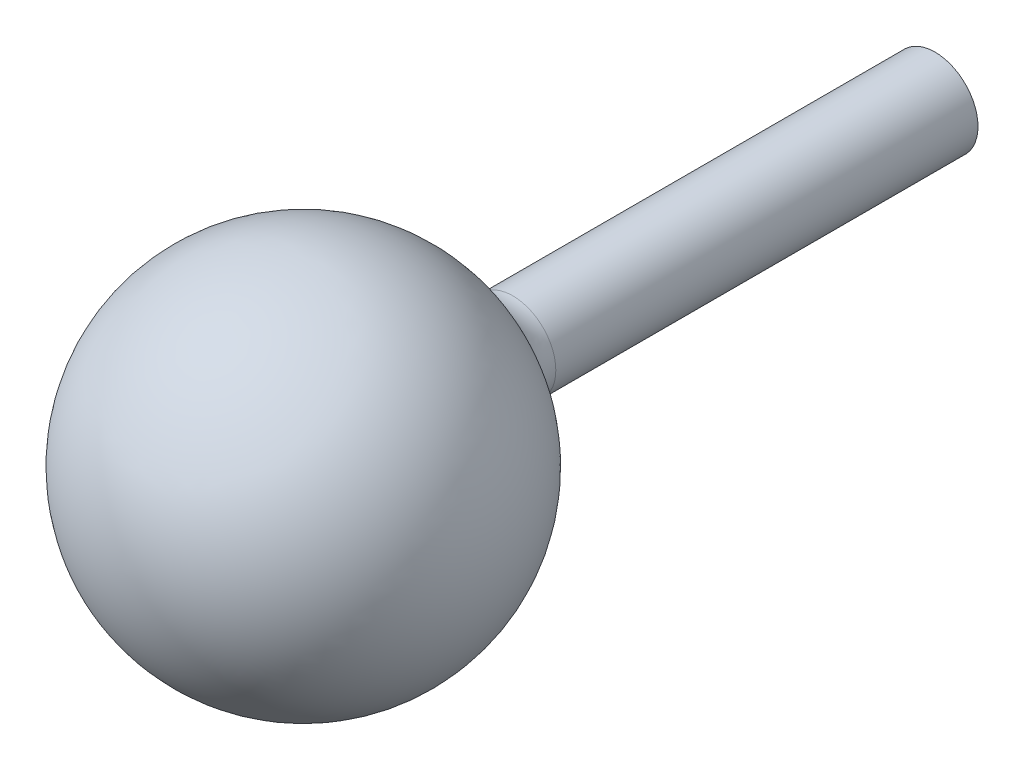
SolidWorks part; units mm, degrees
ref_plane "Front Plane" through (0, 0, 0) normal (0, 0, 1) x (1, 0, 0)
ref_plane "Top Plane" through (0, 0, 0) normal (0, 1, 0) x (1, 0, 0)
ref_plane "Right Plane" through (0, 0, 0) normal (1, 0, 0) x (0, 0, -1)
sketch "Sketch1" plane through (0, 0, 0) normal (0, 0, 1) x (1, 0, 0)
  circle A0 centre (0, 0) radius 6
  dimension "D1" = 12
extrude "Boss-Extrude1" add sketch "Sketch1" along normal blind 63.5
sketch "Sketch2" plane through (0, 0, 0) normal (1, 0, 0) x (0, 0, -1)
  line L0 (-63.5, 0) -> (-113.5812, 0)
  line L1 (-63.5, 6) -> (-63.5, -6) construction
  line L2 (-63.5, 6) -> (-63.5, 0)
  arc A1 (-113.5812, 0) -> (-63.5, 6) centre (-88.1812, 0) cw
  dimension "D1" = 25.4
revolve "Revolve1" add sketch "Sketch2" angle 360 about L0
sketch "Sketch3" plane through (0, 0, 0) normal (0, 0, -1) x (-1, 0, 0)
  line L1 (-0.7, 1.1) -> (0.7, 1.1)
  line L2 (-0.7, 1.1) -> (-0.7, -1.1)
  line L3 (-0.7, -1.1) -> (0.7, -1.1)
  line L4 (0.7, 1.1) -> (0.7, -1.1)
  point P2 (0.7, 0)
  point P5 (0, 1.1)
  dimension "D1" = 1.4
  dimension "D2" = 2.2
extrude "Cut-Extrude1" cut sketch "Sketch3" against normal blind 50.8
fillet "Fillet1" radius 6.35 1 edges at (6, 0, 63.5)
